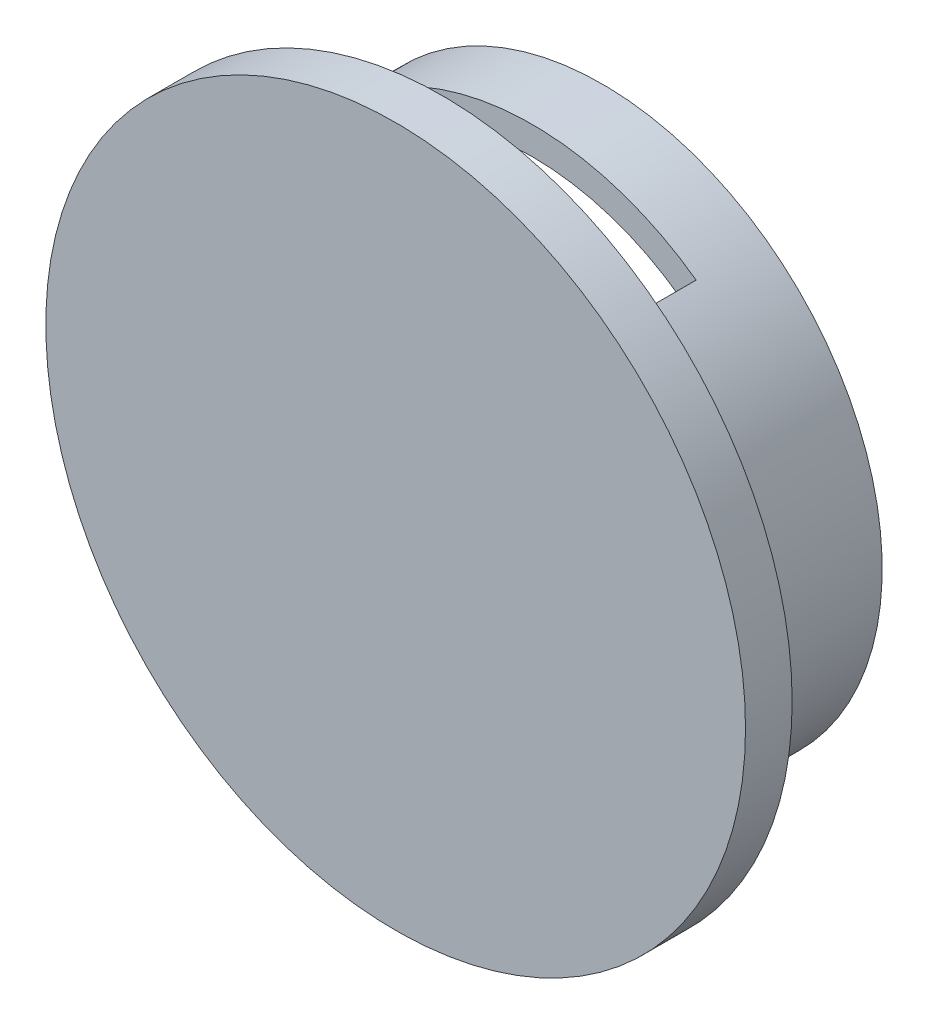
SolidWorks part; units mm, degrees
ref_plane "前视基准面" through (0, 0, 0) normal (0, 0, 1) x (1, 0, 0)
ref_plane "上视基准面" through (0, 0, 0) normal (0, 1, 0) x (1, 0, 0)
ref_plane "右视基准面" through (0, 0, 0) normal (1, 0, 0) x (0, 0, -1)
other "Configuration Table"
sketch "草图2" plane through (0, 0, 0) normal (0, 0, 1) x (1, 0, 0)
  circle A0 centre (-40.1511, 28.7306) radius 75
  dimension "D1" = 150
extrude "凸台-拉伸1" add sketch "草图2" along normal blind 10 contours A0
sketch "草图3" plane through (0, 0, 0) normal (0, 0, -1) x (-1, 0, 0)
  circle A0 centre (40.1511, 28.7306) radius 60
  circle A1 centre (40.1511, 28.7306) radius 75 construction
  dimension "D1" = 120
extrude "凸台-拉伸3" add sketch "草图3" along normal blind 34.3 contours A0
shell "抽壳2" thickness 6
sketch "草图4" plane through (0, 0, 4) normal (0, 0, -1) x (-1, 0, 0)
  circle A0 centre (40.1511, 28.7306) radius 42.5
  circle A1 centre (40.1511, 28.7306) radius 75 construction
  point P4 (40.1511, 71.2306)
  point P6 (82.6511, 28.7306)
  point P8 (40.1511, -13.7694)
  point P10 (-2.3489, 28.7306)
  dimension "D1" = 85
  dimension "D2" = 0
sketch "草图5" plane through (0, 0, -34.3) normal (0, 0, -1) x (-1, 0, 0)
  line L0 (5.0392, 77.384) -> (5.0392, 69.7568)
  line L1 (75.2631, 77.384) -> (75.2631, 68.1729)
  line L2 (5.0392, -12.2956) -> (5.0392, -19.9228)
  line L3 (75.9342, -11.7117) -> (75.9342, -19.4314)
  arc A0 (5.0392, -12.2956) -> (75.9342, -11.7117) centre (40.1511, 28.7306) ccw
  circle A1 centre (40.1511, 28.7306) radius 54 construction
  arc A2 (5.0392, -19.9228) -> (75.9342, -19.4314) centre (40.1511, 28.7306) ccw
  circle A3 centre (40.1511, 28.7306) radius 60 construction
  circle A4 centre (40.1511, 28.7306) radius 60 construction
  arc A5 (5.0392, 69.7568) -> (75.2631, 69.7568) centre (40.1511, 28.7306) cw
  circle A6 centre (40.1511, 28.7306) radius 54 construction
  arc A7 (5.0392, 77.384) -> (75.2631, 77.384) centre (40.1511, 28.7306) cw
  circle M5 centre (40.1511, 28.7306) radius 54
  circle M6 centre (40.1511, 28.7306) radius 60
extrude "切除-拉伸2" cut sketch "草图5" against normal blind 25 contours L1 L0 M6 M5 | L3 L2 M5 M6
sketch "草图6" plane through (0, 0, -34.3) normal (0, 0, -1) x (-1, 0, 0)
  line L0 (5.0392, 77.384) -> (5.0392, 69.7568)
  line L1 (75.2631, 77.384) -> (75.2631, 69.7568)
  line L2 (75.9342, -11.7117) -> (75.9342, -19.4314)
  line L3 (5.0392, -12.2956) -> (5.0392, -19.9228)
  arc A0 (5.0392, 69.7568) -> (75.2631, 69.7568) centre (40.1511, 28.7306) cw
  arc A1 (5.0392, 77.384) -> (75.2631, 77.384) centre (40.1511, 28.7306) cw
  arc A2 (5.0392, -12.2956) -> (75.9342, -11.7117) centre (40.1511, 28.7306) ccw
  arc A3 (5.0392, -19.9228) -> (75.9342, -19.4314) centre (40.1511, 28.7306) ccw
  arc A4 (5.0392, -19.9228) -> (75.9342, -19.4314) centre (40.1511, 28.7306) ccw construction
  circle A5 centre (40.1511, 28.7306) radius 60 construction
extrude "凸台-拉伸4" add sketch "草图6" against normal blind 15 contours L1 A0 L0 A1 | L3 A3 L2 A2
hole_wizard "M3.5 螺纹孔1" positions "草图4" profile "草图10" tap size "M3.5" standard "GB"
sketch "草图10" plane through (2.3489, 28.7306, 4) normal (1, 0, 0) x (0, 1, 0)
  line L0 (0, 0) -> (0, 5.8712)
  line L1 (0, 5.8712) -> (1.45, 5)
  line L2 (1.45, 5) -> (1.45, 0.325)
  line L3 (1.45, 0.325) -> (1.775, 0)
  line L5 (1.775, 0) -> (0, 0)
  line L6 (-1.45, 0.325) -> (-1.775, 0) construction
  line L10 (0, 5.8712) -> (-1.45, 5) construction
  line L11 (0, -6.35) -> (0, 107.95) construction
  dimension "螺纹孔钻头直径" = 2.9
  dimension "螺纹孔钻头深度" = 5
  dimension "近端锥形沉头孔直径" = 3.55
  dimension "近端锥形沉头孔角度" = 90
  dimension "导头角度" = 118
pattern_circular "阵列(圆周)1" count 4 every 45 about axis through (-40.1511, 28.7306, 0) along (0, 0, 1) of "M3.5 螺纹孔1"
